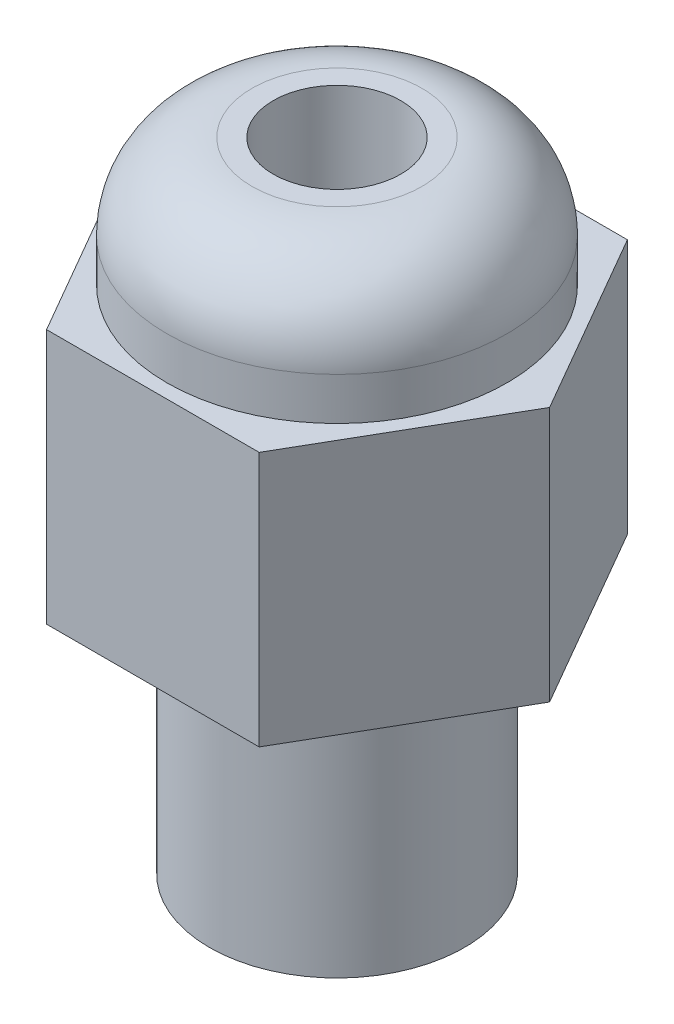
SolidWorks part; units mm, degrees
ref_plane "Front Plane" through (0, 0, 0) normal (0, 0, 1) x (1, 0, 0)
ref_plane "Top Plane" through (0, 0, 0) normal (0, 1, 0) x (1, 0, 0)
ref_plane "Right Plane" through (0, 0, 0) normal (1, 0, 0) x (0, 0, -1)
sketch "Sketch2" plane through (0, 0, 0) normal (0, 1, 0) x (1, 0, 0)
  line L1 (5, 0) -> (2.5, 4.3301)
  line L2 (2.5, 4.3301) -> (-2.5, 4.3301)
  line L3 (-2.5, 4.3301) -> (-5, 0)
  line L4 (-5, 0) -> (-2.5, -4.3301)
  line L5 (-2.5, -4.3301) -> (2.5, -4.3301)
  line L6 (2.5, -4.3301) -> (5, 0)
  circle A0 centre (0, 0) radius 4.3301 construction
  circle A1 centre (0, 0) radius 1.5
  dimension "D2" = 3
  dimension "D1" = 5
extrude "Boss-Extrude1" add sketch "Sketch2" along normal blind 6
sketch "Sketch3" plane through (0, 6, 0) normal (0, 1, 0) x (1, 0, 0)
  circle A0 centre (0, 0) radius 1.5
  circle A1 centre (0, 0) radius 4
  dimension "D1" = 8
extrude "Boss-Extrude2" add sketch "Sketch3" along normal blind 3
fillet "Fillet1" radius 2 1 edges at (0, 9, 4)
sketch "Sketch4" plane through (0, 0, 0) normal (0, -1, 0) x (1, 0, 0)
  circle A0 centre (0, 0) radius 1.5
  circle A1 centre (0, 0) radius 3
  dimension "D1" = 6
extrude "Boss-Extrude3" add sketch "Sketch4" along normal blind 6
